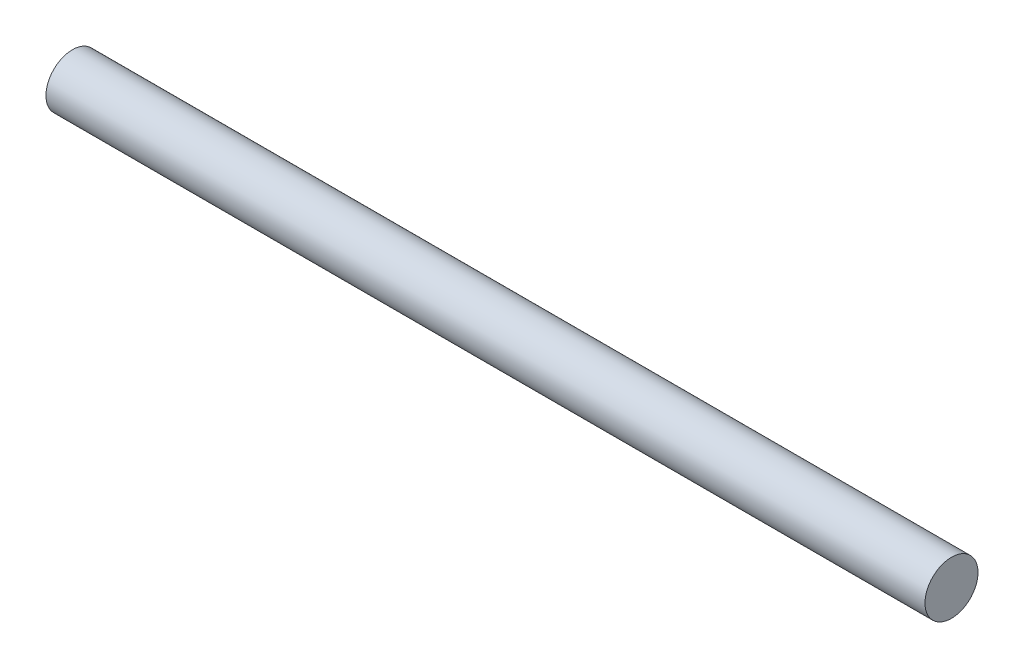
SolidWorks part; units mm, degrees
ref_plane "Front Plane" through (0, 0, 0) normal (0, 0, 1) x (1, 0, 0)
ref_plane "Top Plane" through (0, 0, 0) normal (0, 1, 0) x (1, 0, 0)
ref_plane "Right Plane" through (0, 0, 0) normal (1, 0, 0) x (0, 0, -1)
sketch "Sketch1" plane through (0, 0, 0) normal (1, 0, 0) x (0, 0, -1)
  circle A0 centre (0, 0) radius 2.413
extrude "Boss-Extrude1" add sketch "Sketch1" along normal blind 80
